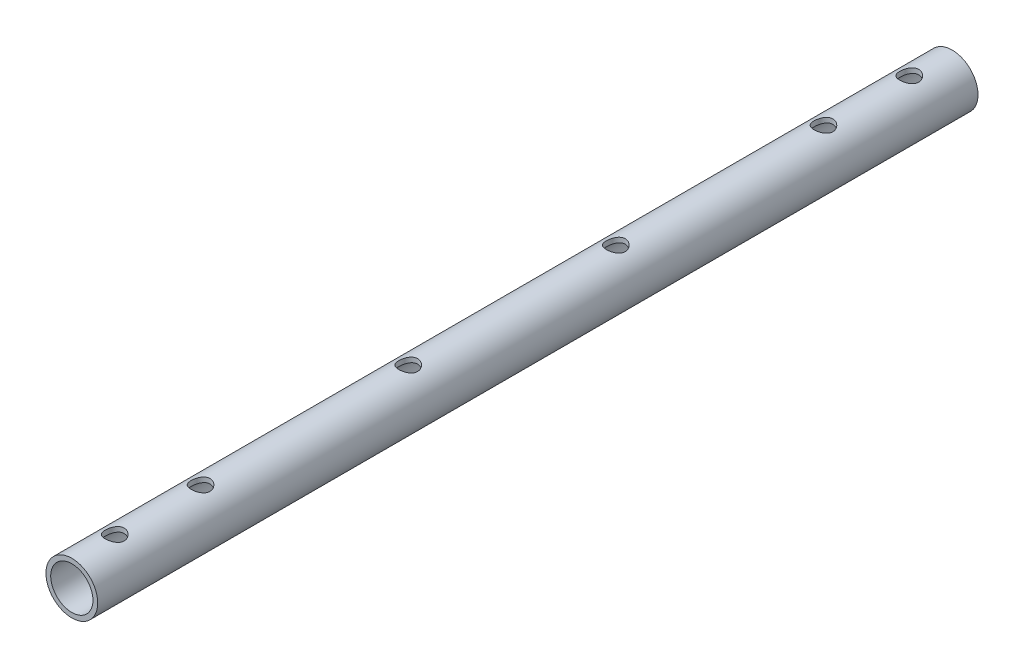
SolidWorks part; units mm, degrees
material "ASTM A36 Steel"
ref_plane "Front Plane" through (0, 0, 0) normal (0, 0, 1) x (1, 0, 0)
ref_plane "Top Plane" through (0, 0, 0) normal (0, 1, 0) x (1, 0, 0)
ref_plane "Right Plane" through (0, 0, 0) normal (1, 0, 0) x (0, 0, -1)
sketch "Sketch1" plane through (0, 0, 0) normal (0, 0, 1) x (1, 0, 0)
  circle A0 centre (0, 0) radius 30.15
  circle A1 centre (0, 0) radius 24.61
  dimension "D1" = 60.3
  dimension "D2" = 49.22
extrude "Boss-Extrude1" add sketch "Sketch1" along normal blind 1026
sketch "Sketch2" plane through (0, 0, 0) normal (0, 1, 0) x (1, 0, 0)
  line L0 (-30.15, -1026) -> (30.15, -1026) construction
  line L1 (30.15, 0) -> (-30.15, 0) construction
  circle A0 centre (0, -976) radius 11
  circle A1 centre (0, -876) radius 11
  circle A2 centre (0, -50) radius 11
  circle A3 centre (0, -150) radius 11
  dimension "D1" = 22
  dimension "D2" = 22
  dimension "D3" = 50
  dimension "D4" = 100
  dimension "D5" = 22
  dimension "D6" = 22
  dimension "D7" = 50
  dimension "D8" = 100
extrude "Cut-Extrude1" cut sketch "Sketch2" against normal through all both and the other way through all
sketch "Sketch3" plane through (0, 0, 0) normal (0, 1, 0) x (1, 0, 0)
  circle A0 centre (0, -392) radius 11
  circle A2 centre (0, -634) radius 11
  circle A3 centre (0, -876) radius 11 construction
  dimension "D1" = 22
  dimension "D2" = 22
  dimension "D3" = 242
  dimension "D4" = 242
extrude "Cut-Extrude2" cut sketch "Sketch3" against normal through all both and the other way through all
